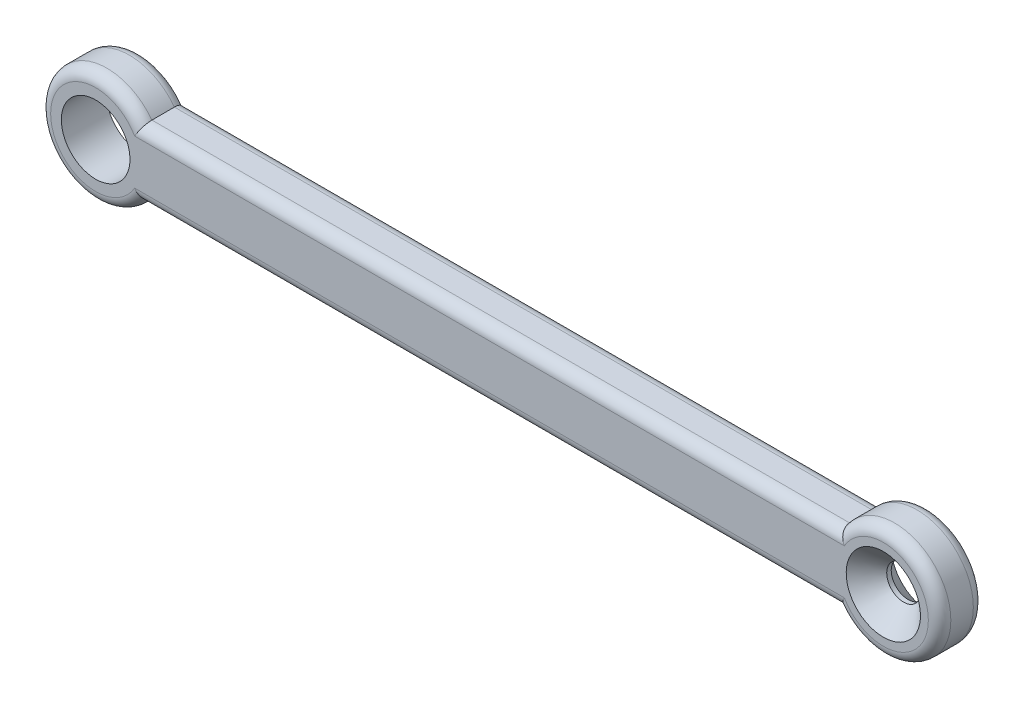
SolidWorks part; units mm, degrees
material "PET"
ref_plane "Plan de face" through (0, 0, 0) normal (0, 0, 1) x (1, 0, 0)
ref_plane "Plan de dessus" through (0, 0, 0) normal (0, 1, 0) x (1, 0, 0)
ref_plane "Plan de droite" through (0, 0, 0) normal (1, 0, 0) x (0, 0, -1)
ref_plane "Plan1" through (0, 2, 0) normal (0, 1, 0) x (1, 0, 0)
sketch "Esquisse1" plane through (0, 2, 0) normal (0, 0, -1) x (1, 0, 0)
  line L0 (47.7089, 2) -> (0, 2) construction
  line L1 (-47.7089, 5) -> (0, 5) construction
  line L2 (0, 9.7076) -> (0, -6.7613) construction
  line L3 (-47.7089, 2) -> (0, 2) construction
  line L4 (-31, -1) -> (31, -1)
  line L5 (-31, 5) -> (31, 5)
  line L6 (-47.7089, -1) -> (0, -1) construction
  arc A0 (31, 5) -> (31, -1) centre (35, 2) cw
  arc A1 (-31, 5) -> (-31, -1) centre (-35, 2) ccw
  dimension "D1" = 70
  dimension "D2" = 5
  dimension "D3" = 3
  dimension "D4" = 3
extrude "Boss.-Extru.1" add sketch "Esquisse1" against normal blind 4
hole_wizard "Diamètre du perçage Ø6.1 (6.1)1" positions "Esquisse3" profile "Esquisse2" hole size "Ø6.1" standard "Ansi Metric" end condition through all
sketch "Esquisse3" plane through (0, 0, 4) normal (0, 0, 1) x (-1, 0, 0)
  point P0 (35, 0)
sketch "Esquisse2" plane through (-35, 0, 4) normal (1, 0, 0) x (0, -1, 0)
  line L0 (0, 0) -> (0, 4)
  line L1 (0, 4) -> (3.05, 4)
  line L2 (3.05, 4) -> (3.05, 0)
  line L5 (3.05, 0) -> (0, 0)
  line L11 (0, -6.35) -> (0, 107.95) construction
  dimension "Diamètre du perçage jusqu'au prochain" = 6.1
  dimension "Profondeur du perçage jusqu'au prochain" = 4
hole_wizard "Fraisage pour vis à tête fraisée M2.51" positions "Esquisse5" profile "Esquisse4" countersink size "M2.5" standard "Ansi Metric" end condition through all
sketch "Esquisse5" plane through (0, 0, 4) normal (0, 0, 1) x (-1, 0, 0)
  point P0 (-35, 0)
sketch "Esquisse4" plane through (35, 0, 4) normal (1, 0, 0) x (0, -1, 0)
  line L0 (0, 0) -> (0, 4)
  line L1 (0, 4) -> (3.3, 4)
  line L2 (1.5, 2.2) -> (1.5, 1.8)
  line L3 (1.5, 1.8) -> (3.3, 0)
  line L5 (3.3, 0) -> (0, 0)
  line L6 (-1.5, 1.8) -> (-3.3, 0) construction
  line L7 (3.3, 4) -> (1.5, 2.2)
  line L8 (-3.3, 4) -> (-1.5, 2.2) construction
  line L11 (0, -6.35) -> (0, 107.95) construction
  dimension "Diamètre du perçage jusqu'au prochain" = 3
  dimension "Profondeur du perçage jusqu'au prochain" = 4
  dimension "Diamètre du fraisage entrant" = 6.6
  dimension "Angle du fraisage entrant" = 90
  dimension "Diamètre du fraisage débouchant" = 6.6
  dimension "Angle du fraisage débouchant" = 90
fillet "Congé1" radius 1 8 edges at (-40, 0, 4) (-40, 0, 0) (0, 3, 4) (0, -3, 4) (40, 0, 4) (40, 0, 0) (0, 3, 0) (0, -3, 0)
